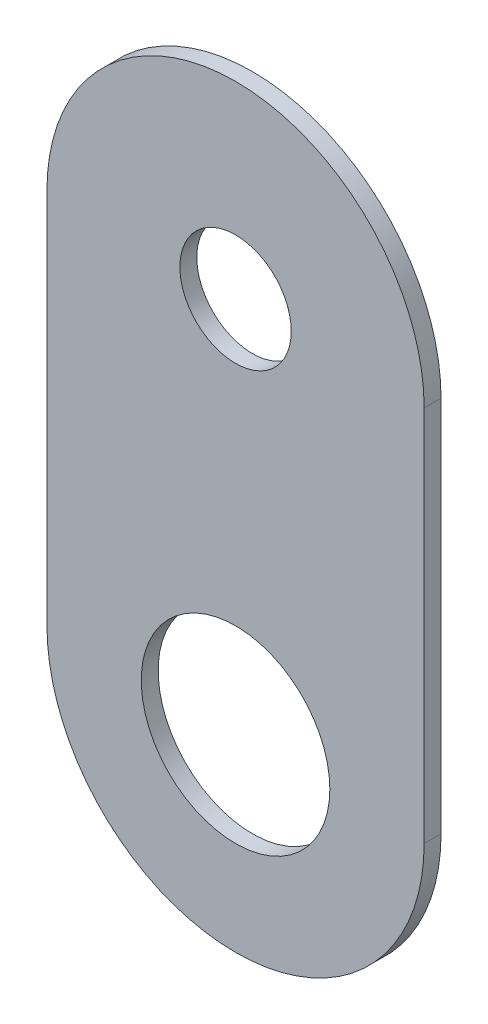
SolidWorks part; units mm, degrees
ref_plane "Front Plane" through (0, 0, 0) normal (0, 0, 1) x (1, 0, 0)
ref_plane "Top Plane" through (0, 0, 0) normal (0, 1, 0) x (1, 0, 0)
ref_plane "Right Plane" through (0, 0, 0) normal (1, 0, 0) x (0, 0, -1)
sketch "Sketch1" plane through (0, 0, 0) normal (0, 0, 1) x (1, 0, 0)
  line L1 (-25.4, 0) -> (25.4, 0)
  line L2 (-25.4, 0) -> (-25.4, -50.8)
  line L3 (-25.4, -50.8) -> (25.4, -50.8)
  line L4 (25.4, 0) -> (25.4, -50.8)
  circle A0 centre (0, 0) radius 7.4981
  circle A1 centre (0, 0) radius 25.4
  circle A2 centre (0, -50.8) radius 12.7
  circle A3 centre (0, -50.8) radius 25.4
  dimension "D1" = 7.4981
  dimension "D2" = 25.4
  dimension "D4" = 25.4
  dimension "D3" = 50.8
extrude "Boss-Extrude1" add sketch "Sketch1" along normal blind 2.2761 contours L1 A1 A0 | A3 L4 A1 | A3 A1 L2 | L1 A1 A0 | L3 A3 A2 | L3 A3 A2
equation "\"sf\"= 4"
equation "\"F\"= 600"
equation "\"E\"= 15199999.87"
equation "\"W\"= 2 * \"F\""
equation "\"stress_y\" = 120000"
equation "\"delt_max\"= 0.005"
equation "\"stress\"= \"stress_y\" / \"sf\""
equation "\"delt\"= \"delt_max\" / \"sf\""
equation "\"Z\"= \"W\" / ( 2 * \"stress\" )"
equation "\"r1\"= ( ( 4 * \"Z\" ) / PI ) ^ ( 1 / 3 )"
equation "\"L1\"= 1"
equation "\"I1\"= ( 5 * \"W\" * ( \"L1\" ^ 3 ) ) / ( 384 * \"E\" * \"delt\" )"
equation "\"r2\"= ( ( \"I1\" * 4 ) / PI ) ^ ( 1 / 4 )"
equation "\"L2\"= 2 * \"r3\""
equation "\"d2\"= 1"
equation "\"A1\"= \"F\" / \"stress\""
equation "\"r3\" =1"
equation "\"w1\" = \"A1\" / ( \"r3\" - \"r\" )"
equation "\"A2\"= ( \"F\" * \"L2\" ) / ( \"E\" * \"delt\" )"
equation "\"w2\" = \"A2\" / ( \"r3\" - \"r\" )"
equation "\"D1@Sketch1\"=\"r\""
equation "\"D2@Sketch1\"= \"r3\""
equation "\"D3@Sketch1\"= \"L2\""
equation "\"D1@Boss-Extrude1\"= \"w2\""
equation "\"r\"= \"r1\" + 0.001"
equation "\"D4@Sketch1\"= \"d2\""
